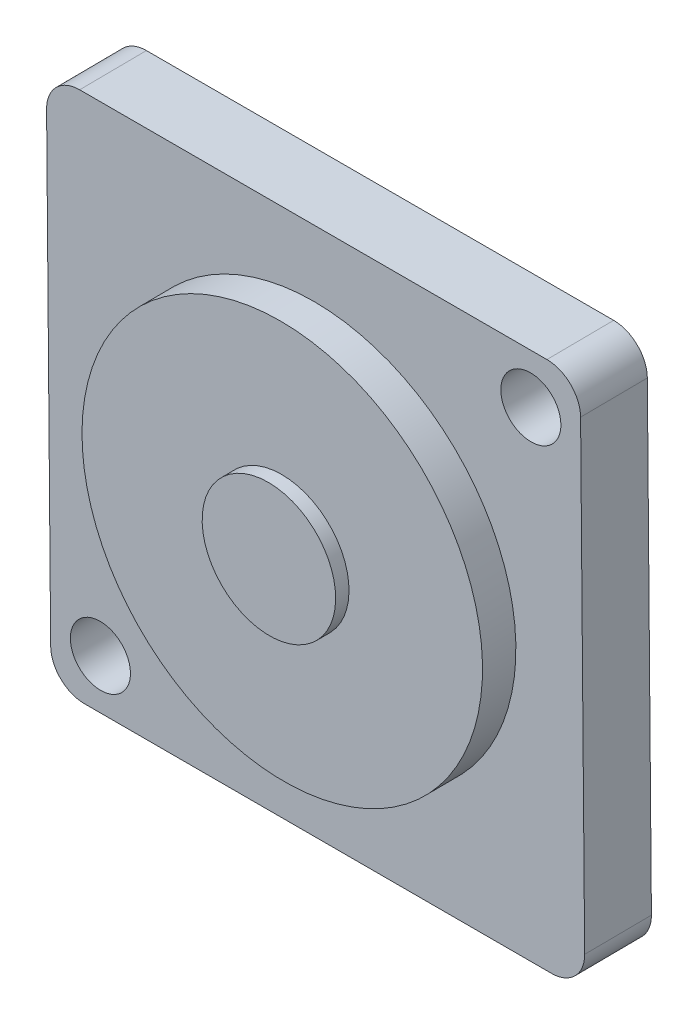
SolidWorks part; units mm, degrees
material "Cast Alloy Steel"
ref_plane "Front Plane" through (0, 0, 0) normal (0, 0, 1) x (1, 0, 0)
ref_plane "Top Plane" through (0, 0, 0) normal (0, 1, 0) x (1, 0, 0)
ref_plane "Right Plane" through (0, 0, 0) normal (1, 0, 0) x (0, 0, -1)
sketch "Sketch4" plane through (0, 0, 0) normal (0, 0, 1) x (1, 0, 0)
  line L1 (-20, 20) -> (20, 20)
  line L2 (-20, 20) -> (-20, -20)
  line L3 (-20, -20) -> (20, -20)
  line L4 (20, 20) -> (20, -20)
  line L5 (-20, 20) -> (20, -20) construction
  line L6 (-20, -20) -> (20, 20) construction
  point P0 (0, 0)
  point P4 (0, 0)
  point P8 (0, 0)
  dimension "D1" = 40
  dimension "D2" = 40
extrude "Boss-Extrude2" add sketch "Sketch4" along normal blind 4.9995 and the other way blind 0.0001
sketch "Sketch6" plane through (0, 0, 4.9995) normal (0, 0, 1) x (1, 0, 0)
  circle A0 centre (0, 0) radius 15
  dimension "D1" = 30
extrude "Boss-Extrude3" add sketch "Sketch6" along normal blind 2.5
sketch "Sketch7" plane through (0, 0, 7.4995) normal (0, 0, 1) x (1, 0, 0)
  circle A0 centre (0, 0) radius 5
  dimension "D1" = 10
extrude "Boss-Extrude4" add sketch "Sketch7" along normal blind 1 contours A0
sketch "Sketch8" plane through (0, 0, 8.4995) normal (0, 0, 1) x (1, 0, 0)
  circle A0 centre (0, 0) radius 4
  dimension "D1" = 8
sketch "Sketch9" plane through (0, 0, 4.9995) normal (0, 0, 1) x (1, 0, 0)
  line L0 (-16.263, 16.263) -> (-20, 16.263) construction
  line L1 (-20, 20) -> (-20, -20) construction
  line L2 (-16.263, 16.263) -> (-16.263, 20) construction
  line L3 (20, 20) -> (-20, 20) construction
  circle A0 centre (-16.263, 16.263) radius 2.25
  dimension "D1" = 4.5
extrude "Cut-Extrude1" cut sketch "Sketch9" against normal blind 5 contours A0
sketch "Sketch10" plane through (0, 0, 4.9995) normal (0, 0, 1) x (1, 0, 0)
  line L0 (16.263, -16.263) -> (16.263, -20) construction
  line L1 (-20, -20) -> (20, -20) construction
  line L2 (16.263, -16.263) -> (20, -16.263) construction
  line L3 (20, -20) -> (20, 20) construction
  circle A0 centre (16.263, -16.263) radius 2.25
  dimension "D1" = 4.5
  dimension "D2" = 3.737
extrude "Cut-Extrude2" cut sketch "Sketch10" against normal blind 5 contours A0
fillet "Fillet2" radius 2.5 4 edges at (-20, 20, 2.4997) (-20, -20, 2.4997) (20, -20, 2.4997) (20, 20, 2.4997)
move or copy body "Body-Move/Copy2" bodies to move or copy 109 copy no rotation origin (0.0183, 0.0183, 0.0002) rotation axis (0.0044, 0.0044, -1) rotation angle 90.001
